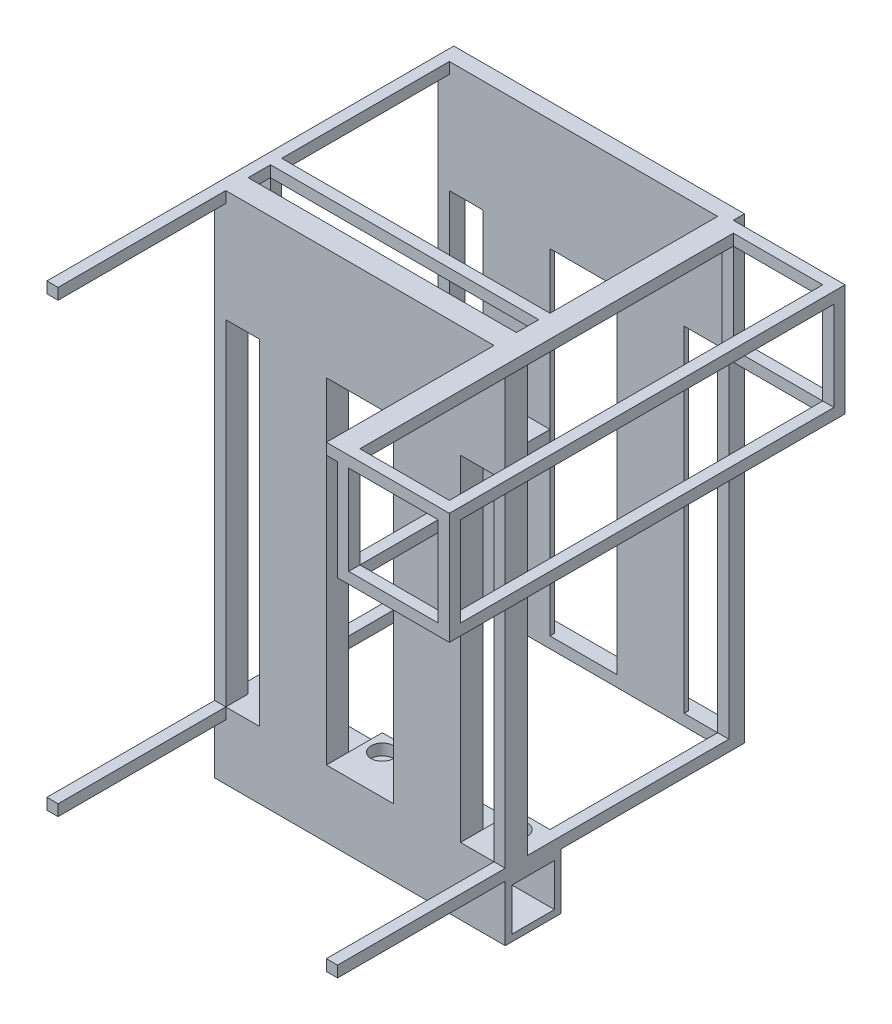
SolidWorks part; units mm, degrees
ref_plane "Front Plane" through (0, 0, 0) normal (0, 0, 1) x (1, 0, 0)
ref_plane "Top Plane" through (0, 0, 0) normal (0, 1, 0) x (1, 0, 0)
ref_plane "Right Plane" through (0, 0, 0) normal (1, 0, 0) x (0, 0, -1)
sketch "Sketch1" plane through (0, 0, 0) normal (0, 0, 1) x (1, 0, 0)
  line L0 (50, -50) -> (1250, -50)
  line L1 (0, 0) -> (1300, 0)
  line L2 (0, 0) -> (0, -1600)
  line L3 (0, -1600) -> (1300, -1600)
  line L4 (1300, 0) -> (1300, -1600)
  line L5 (1250, -50) -> (1250, -1550)
  line L6 (50, -1550) -> (1250, -1550)
  line L7 (50, -50) -> (50, -1550)
  dimension "D1" = 1300
  dimension "D2" = 1600
  dimension "D3" = 50
extrude "Boss-Extrude1" add sketch "Sketch1" along normal blind 100
sketch "Sketch2" plane through (0, -50, 0) normal (0, -1, 0) x (1, 0, 0)
  line L0 (650, 100) -> (650, 0) construction
  line L1 (1250, 100) -> (50, 100) construction
  line L2 (1250, 0) -> (50, 0) construction
  line L3 (200, 100) -> (500, 100)
  line L4 (1100, 0) -> (800, 0)
  line L5 (1100, 0) -> (1100, 100)
  line L6 (1100, 100) -> (800, 100)
  line L7 (800, 0) -> (800, 100)
  line L8 (500, 0) -> (500, 100)
  line L9 (200, 0) -> (500, 0)
  line L10 (200, 0) -> (200, 100)
  dimension "D1" = 300
  dimension "D2" = 150
extrude "Boss-Extrude2" add sketch "Sketch2" along normal blind 1500
sketch "Sketch3" plane through (0, 0, 0) normal (0, 0, -1) x (-1, 0, 0)
  line L0 (-1300, 0) -> (0, 0) construction
  line L1 (-1250, -50) -> (-1100, -50)
  line L2 (-1250, -50) -> (-1250, 0)
  line L3 (-1250, 0) -> (-1100, 0)
  line L4 (-1100, -50) -> (-1100, 0)
  line L5 (0, -1600) -> (-1300, -1600) construction
  line L6 (-800, -50) -> (-504.1447, -50)
  line L7 (-800, -50) -> (-800, 0)
  line L8 (-800, 0) -> (-504.1447, 0)
  line L9 (-504.1447, -50) -> (-504.1447, 0)
  line L10 (-200, -50) -> (-50, -50)
  line L11 (-200, -50) -> (-200, 0)
  line L12 (-200, 0) -> (-50, 0)
  line L13 (-50, -50) -> (-50, 0)
  line L14 (-1250, -1550) -> (-1100, -1550)
  line L15 (-1250, -1550) -> (-1250, -1600)
  line L16 (-1250, -1600) -> (-1100, -1600)
  line L17 (-1100, -1550) -> (-1100, -1600)
  line L19 (-800, -1550) -> (-500, -1550)
  line L20 (-800, -1550) -> (-800, -1600)
  line L21 (-800, -1600) -> (-500, -1600)
  line L22 (-500, -1550) -> (-500, -1600)
  line L23 (-200, -1550) -> (-50, -1550)
  line L24 (-200, -1550) -> (-200, -1600)
  line L25 (-200, -1600) -> (-50, -1600)
  line L26 (-50, -1550) -> (-50, -1600)
extrude "Boss-Extrude3" add sketch "Sketch3" along normal blind 150
sketch "Sketch4" plane through (0, -1600, 0) normal (0, -1, 0) x (1, 0, 0)
  line L0 (500, -150) -> (500, 0) construction
  line L1 (800, -150) -> (500, -150) construction
  line L2 (200, -150) -> (50, -150) construction
  circle A0 centre (1175, -75) radius 50
  circle A1 centre (725, -75) radius 50
  circle A2 centre (575, -75) radius 50
  circle A3 centre (126.5412, -75) radius 50
  dimension "D1" = 100
  dimension "D2" = 100
  dimension "D3" = 100
  dimension "D4" = 100
  dimension "D5" = 150
  dimension "D6" = 75
  dimension "D7" = 75
  dimension "D8" = 75
  dimension "D9" = 75
extrude "Cut-Extrude1" cut sketch "Sketch4" against normal blind 50
sketch "Sketch5" plane through (0, 0, 0) normal (-1, 0, 0) x (0, 0, 1)
  line L1 (0, 0) -> (100, 0)
  line L2 (0, 0) -> (0, 450)
  line L3 (0, 450) -> (100, 450)
  line L4 (100, 0) -> (100, 450)
  dimension "D1" = 450
extrude "Boss-Extrude6" add sketch "Sketch5" against normal blind 1300
sketch "Sketch6" plane through (0, 0, 100) normal (0, 0, 1) x (1, 0, 0)
  line L0 (650, 450) -> (650, -1600) construction
  line L1 (0, 450) -> (50, 450)
  line L2 (0, 450) -> (0, 400)
  line L3 (0, 400) -> (50, 400)
  line L4 (50, 450) -> (50, 400)
  line L5 (1300, 450) -> (0, 450) construction
  line L6 (0, -1600) -> (1300, -1600) construction
  line L7 (0, -575) -> (1300, -575) construction
  line L8 (0, 450) -> (0, -1600) construction
  line L9 (1300, -1600) -> (1300, 450) construction
  line L10 (1300, 400) -> (1250, 400)
  line L11 (1250, 450) -> (1250, 400)
  line L12 (1300, 450) -> (1250, 450)
  line L13 (1300, 450) -> (1300, 400)
  line L14 (1300, -1600) -> (1300, -1550)
  line L15 (1300, -1600) -> (1250, -1600)
  line L16 (1250, -1600) -> (1250, -1550)
  line L17 (1300, -1550) -> (1250, -1550)
  line L18 (0, -1550) -> (50, -1550)
  line L19 (50, -1600) -> (50, -1550)
  line L20 (0, -1600) -> (50, -1600)
  line L21 (0, -1600) -> (0, -1550)
  dimension "D1" = 50
  dimension "D2" = 50
extrude "Boss-Extrude7" add sketch "Sketch6" along normal blind 750 and the other way blind 1000
sketch "Sketch7" plane through (0, 0, -900) normal (0, 0, -1) x (-1, 0, 0)
  line L1 (0, -1600) -> (-1300, -1600)
  line L2 (0, -1600) -> (0, 450)
  line L3 (0, 450) -> (-1300, 450)
  line L4 (-1300, -1600) -> (-1300, 450)
extrude "Boss-Extrude8" add sketch "Sketch7" along normal blind 20
sketch "Sketch8" plane through (0, 0, -900) normal (0, 0, 1) x (1, 0, 0)
  line L1 (1250, -1550) -> (1100, -1550)
  line L2 (1250, -1550) -> (1250, -50)
  line L3 (1250, -50) -> (1100, -50)
  line L4 (1100, -1550) -> (1100, -50)
  line L5 (800, -1550) -> (500, -1550)
  line L6 (800, -1550) -> (800, -50)
  line L7 (800, -50) -> (500, -50)
  line L8 (500, -1550) -> (500, -50)
  line L9 (200, -1550) -> (50, -1550)
  line L10 (200, -1550) -> (200, -50)
  line L11 (200, -50) -> (50, -50)
  line L12 (50, -1550) -> (50, -50)
extrude "Cut-Extrude2" cut sketch "Sketch8" against normal blind 20
sketch "Sketch9" plane through (0, 400, 0) normal (0, -1, 0) x (1, 0, 0)
  line L0 (0, 850) -> (0, -920) construction
  line L1 (50, -150) -> (0, -150)
  line L2 (50, -150) -> (50, -100)
  line L3 (50, -100) -> (0, -100)
  line L4 (0, -150) -> (0, -100)
  dimension "D1" = 50
extrude "Boss-Extrude9" add sketch "Sketch9" along normal blind 1958
sketch "Sketch10" plane through (1250, 0, 0) normal (-1, 0, 0) x (0, 0, 1)
  line L0 (850, 450) -> (-920, 450) construction
  line L1 (-150, 400) -> (-100, 400)
  line L2 (-150, 400) -> (-150, 450)
  line L3 (-150, 450) -> (-100, 450)
  line L4 (-100, 400) -> (-100, 450)
extrude "Boss-Extrude10" add sketch "Sketch10" along normal up to vertex (1200 mm away)
sketch "Sketch11" plane through (0, 0, -920) normal (0, 0, -1) x (-1, 0, 0)
  line L0 (-1350, 400) -> (-1350, 0)
  line L1 (-1350, 0) -> (-1750, 0)
  line L2 (-1300, 450) -> (-1800, 450)
  line L3 (-1300, 450) -> (-1300, -50)
  line L4 (-1300, -50) -> (-1800, -50)
  line L5 (-1800, 450) -> (-1800, -50)
  line L6 (-1750, 400) -> (-1750, 0)
  line L7 (-1350, 400) -> (-1750, 400)
  dimension "D1" = 500
  dimension "D2" = 500
  dimension "D3" = 50
extrude "Boss-Extrude11" add sketch "Sketch11" against normal blind 1770 contours L0 L1 L6 L7 | L3 L2 L5 L4
sketch "Sketch12" plane through (0, -50, 0) normal (0, -1, 0) x (1, 0, 0)
  line L0 (1750, -870) -> (1750, 800)
  line L1 (1800, -920) -> (1300, -920)
  line L2 (1800, -920) -> (1800, 850)
  line L3 (1800, 850) -> (1300, 850)
  line L4 (1300, -920) -> (1300, 850)
  line L5 (1750, 800) -> (1350, 800)
  line L6 (1350, -870) -> (1350, 800)
  line L7 (1750, -870) -> (1350, -870)
  dimension "D1" = 50
extrude "Cut-Extrude3" cut sketch "Sketch12" against normal blind 500 contours L0 L5 L6 L7
sketch "Sketch13" plane through (1800, 0, 0) normal (1, 0, 0) x (0, 0, -1)
  line L0 (870, 400) -> (870, 0)
  line L1 (920, 450) -> (-850, 450)
  line L2 (920, 450) -> (920, -50)
  line L3 (920, -50) -> (-850, -50)
  line L4 (-850, 450) -> (-850, -50)
  line L5 (870, 0) -> (-800, 0)
  line L6 (-800, 400) -> (-800, 0)
  line L7 (870, 400) -> (-800, 400)
  dimension "D1" = 50
extrude "Cut-Extrude5" cut sketch "Sketch13" against normal blind 500 contours L0 L5 L6 L7
sketch "Sketch14" plane through (1300, 0, 0) normal (1, 0, 0) x (0, 0, -1)
  line L0 (120, -1630) -> (120, -1820)
  line L1 (150, -1600) -> (-100, -1600)
  line L2 (150, -1600) -> (150, -1850)
  line L3 (150, -1850) -> (-100, -1850)
  line L4 (-100, -1600) -> (-100, -1850)
  line L5 (120, -1820) -> (-70, -1820)
  line L6 (-70, -1630) -> (-70, -1820)
  line L7 (120, -1630) -> (-70, -1630)
  dimension "D1" = 250
  dimension "D2" = 30
extrude "Boss-Extrude12" add sketch "Sketch14" against normal up to vertex (1300 mm away)
sketch "Sketch15" plane through (0, 0, -920) normal (0, 0, -1) x (-1, 0, 0)
  line L0 (0, 450) -> (-1800, 450) construction
  line L1 (0, -1600) -> (-1300, -1600)
  line L2 (0, -1600) -> (0, 450)
  line L3 (0, 450) -> (-1300, 450)
  line L4 (-1300, -1600) -> (-1300, 450)
  line L6 (-50, -1550) -> (-1250, -1550)
  line L7 (-50, -1550) -> (-50, 400)
  line L8 (-50, 400) -> (-1250, 400)
  line L9 (-1250, -1550) -> (-1250, 400)
  dimension "D1" = 1950
  dimension "D2" = 1200
extrude "Boss-Extrude13" add sketch "Sketch15" along normal blind 50
sketch "Sketch16" plane through (1300, 0, 0) normal (1, 0, 0) x (0, 0, -1)
  line L0 (970, 450) -> (970, -1600) construction
  line L1 (920, -50) -> (970, -50)
  line L2 (920, -50) -> (920, 400)
  line L3 (920, 400) -> (970, 400)
  line L4 (970, -50) -> (970, 400)
  dimension "D1" = 450
extrude "Cut-Extrude6" cut sketch "Sketch16" against normal blind 50 contours L2 L1 L4 L3
